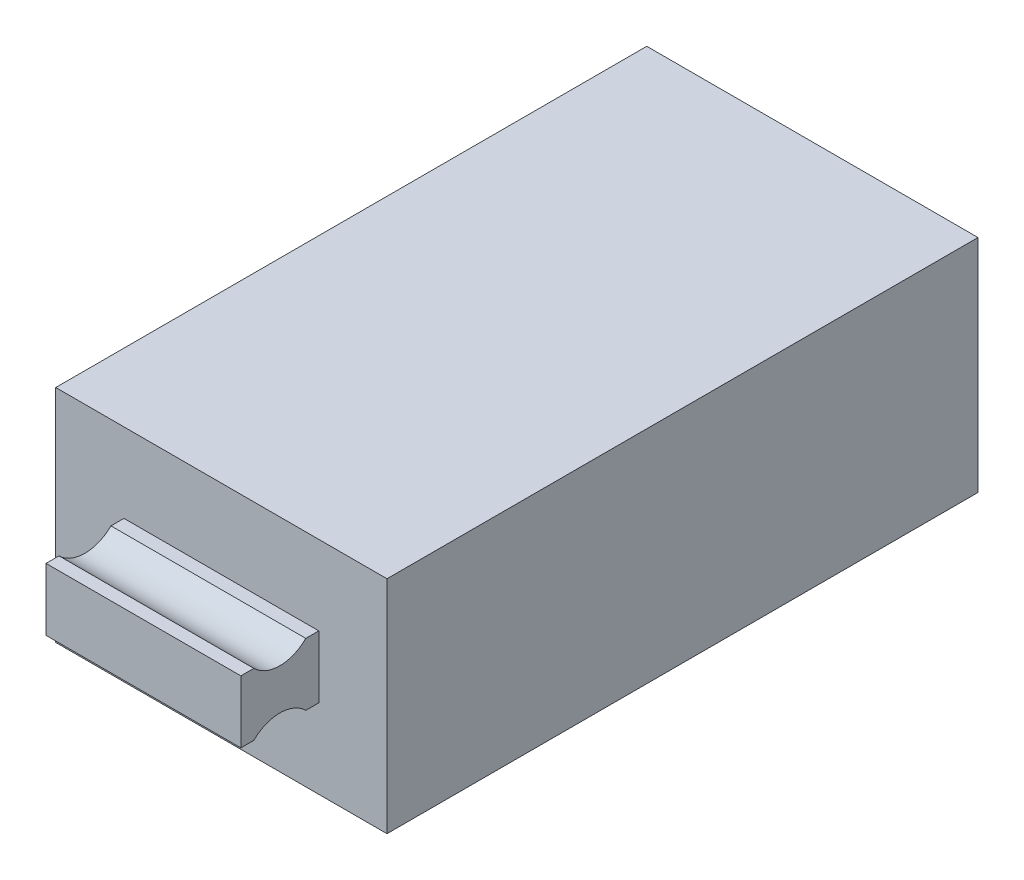
SolidWorks part; units mm, degrees
ref_plane "Front Plane" through (0, 0, 0) normal (0, 0, 1) x (1, 0, 0)
ref_plane "Top Plane" through (0, 0, 0) normal (0, 1, 0) x (1, 0, 0)
ref_plane "Right Plane" through (0, 0, 0) normal (1, 0, 0) x (0, 0, -1)
sketch "Sketch1" plane through (0, 0, 0) normal (0, 0, 1) x (1, 0, 0)
  line L1 (0, 0) -> (51, 0)
  line L2 (0, 0) -> (0, -34)
  line L3 (0, -34) -> (51, -34)
  line L4 (51, 0) -> (51, -34)
  dimension "D1" = 51
  dimension "D2" = 34
extrude "Boss-Extrude1" add sketch "Sketch1" along normal blind 91
sketch "Sketch2" plane through (0, 0, 91) normal (0, 0, 1) x (1, 0, 0)
  line L0 (0, 0) -> (0, -34) construction
  line L1 (10.5, -14) -> (40.5, -14)
  line L2 (10.5, -14) -> (10.5, -20)
  line L3 (10.5, -20) -> (40.5, -20)
  line L4 (40.5, -14) -> (40.5, -20)
  line L5 (51, 0) -> (0, 0) construction
  point P4 (10.5, -17)
  point P7 (0, -17)
  point P8 (25.5, -14)
  point P11 (25.5, 0)
  dimension "D1" = 6
  dimension "D2" = 30
extrude "Boss-Extrude2" add sketch "Sketch2" along normal blind 12
sketch "Sketch3" plane through (10.5, 0, 0) normal (-1, 0, 0) x (0, 0, 1)
  line L0 (91, -12.2) -> (93, -12.2)
  line L1 (91, 0) -> (91, -34) construction
  line L2 (103, -14) -> (103, -12.2)
  line L3 (103, -12.2) -> (101, -12.2)
  line L4 (91, -12.2) -> (91, -14)
  line L5 (93, -12.2) -> (101, -12.2) construction
  line L6 (103, -14) -> (91, -14) construction
  line L7 (91, -14) -> (103, -14) construction
  line L8 (91, -17) -> (103, -17) construction
  line L9 (103, -14) -> (103, -20) construction
  line L10 (91, -20) -> (103, -20) construction
  line L11 (103, -20) -> (103, -21.8)
  line L12 (103, -21.8) -> (101, -21.8)
  line L13 (91, -21.8) -> (93, -21.8)
  line L14 (91, -21.8) -> (91, -20)
  line L15 (91, -14) -> (103, -14)
  line L16 (91, -20) -> (103, -20)
  arc A0 (93, -12.2) -> (101, -12.2) centre (97, -8.2) ccw
  arc A1 (93, -21.8) -> (101, -21.8) centre (97, -25.8) cw
  point P7 (97, -12.2)
  point P13 (97, -14)
  dimension "D1" = 8
  dimension "D2" = 1.8
  dimension "D3" = 4
extrude "Boss-Extrude3" add sketch "Sketch3" against normal up to surface (30 mm away) up to face at (40.5, -17, 97)
